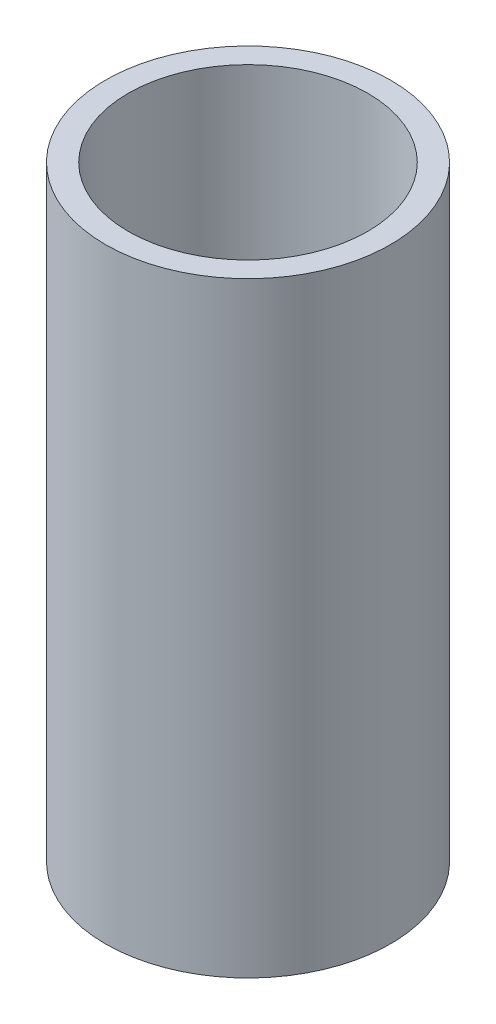
SolidWorks part; units mm, degrees
ref_plane "Front Plane" through (0, 0, 0) normal (0, 0, 1) x (1, 0, 0)
ref_plane "Top Plane" through (0, 0, 0) normal (0, 1, 0) x (1, 0, 0)
ref_plane "Right Plane" through (0, 0, 0) normal (1, 0, 0) x (0, 0, -1)
sketch "Sketch1" plane through (0, 0, 0) normal (0, 0, 1) x (1, 0, 0)
  line L0 (0, 55.1745) -> (0, 0) construction
  line L1 (12.5, 53.12) -> (12.5, 0)
  line L2 (12.5, 53.12) -> (10.5, 53.12)
  line L3 (10.5, 53.12) -> (10.5, 0)
  line L4 (10.5, 0) -> (12.5, 0)
  dimension "D1" = 53.12
  dimension "D2" = 25
  dimension "D3" = 2
revolve "Revolve1" add sketch "Sketch1" angle 360 about L0
